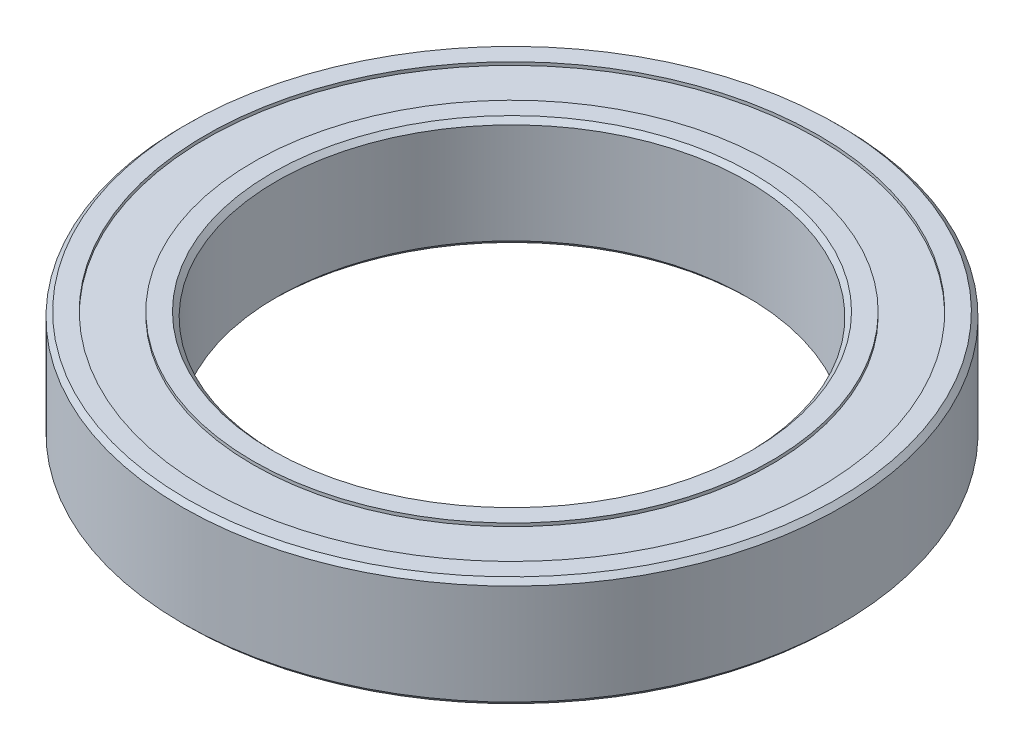
SolidWorks part; units mm, degrees
material "Alloy Steel"
ref_plane "Front Plane" through (0, 0, 0) normal (0, 0, 1) x (1, 0, 0)
ref_plane "Top Plane" through (0, 0, 0) normal (0, 1, 0) x (1, 0, 0)
ref_plane "Right Plane" through (0, 0, 0) normal (1, 0, 0) x (0, 0, -1)
sketch "Sketch1" plane through (0, 0, 0) normal (0, 1, 0) x (1, 0, 0)
  circle A0 centre (0, 0) radius 15
  circle A1 centre (0, 0) radius 21
  dimension "D1" = 42
  dimension "D2" = 30
extrude "Boss-Extrude1" add sketch "Sketch1" along normal blind 7
sketch "Sketch2" plane through (0, 7, 0) normal (0, 1, 0) x (1, 0, 0)
  circle A2 centre (0, 0) radius 16.5
  circle A3 centre (0, 0) radius 16.5
  circle A5 centre (0, 0) radius 19.5
  circle A6 centre (0, 0) radius 19.5
  dimension "D1" = 1.5
  dimension "D2" = 1.5
extrude "Cut-Extrude1" cut sketch "Sketch2" against normal blind 0.2
chamfer "Chamfer1" distance 0.3 angle 45 4 edges at (0, 0, 21) (0, 7, 21) (0, 0, 15) (0, 7, 15)
sketch "Sketch3" plane through (0, 0, 0) normal (0, -1, 0) x (1, 0, 0)
  circle A0 centre (0, 0) radius 16.5 construction
  circle A1 centre (0, 0) radius 19.5
  circle A2 centre (0, 0) radius 19.5
  circle A3 centre (0, 0) radius 16.5
  dimension "D1" = 0
extrude "Cut-Extrude2" cut sketch "Sketch3" against normal blind 0.2
